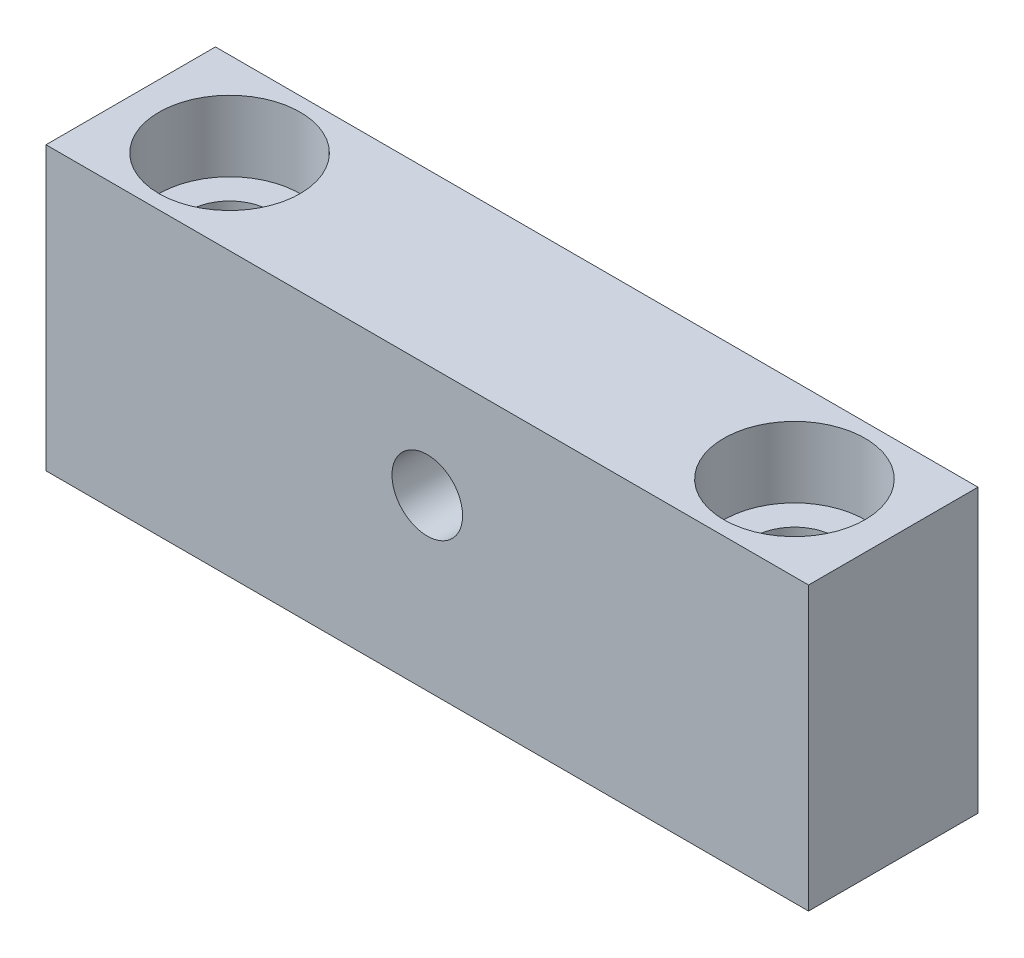
SolidWorks part; units mm, degrees
material "S45C表面镀硬铬"
ref_plane "前基準面" through (0, 0, 0) normal (0, 0, 1) x (1, 0, 0)
ref_plane "上基準面" through (0, 0, 0) normal (0, 1, 0) x (1, 0, 0)
ref_plane "右基準面" through (0, 0, 0) normal (1, 0, 0) x (0, 0, -1)
sketch "草图1" plane through (0, 0, 0) normal (0, 0, 1) x (1, 0, 0)
  line L1 (0, 0) -> (54, 0)
  line L2 (0, 0) -> (0, 20)
  line L3 (0, 20) -> (54, 20)
  line L4 (54, 0) -> (54, 20)
  dimension "D1" = 54
  dimension "D2" = 20
extrude "凸台-拉伸1" add sketch "草图1" along normal blind 12
hole_wizard "M6 螺纹孔1" positions "草图4" profile "草图5" tap size "M6" standard "ISO" end condition through all
sketch "草图4" plane through (0, 0, 12) normal (0, 0, 1) x (1, 0, 0)
  line L1 (27, 20) -> (27, 0) construction
  line L2 (54, 20) -> (0, 20) construction
  line L3 (0, 0) -> (54, 0) construction
  point P0 (27, 12)
  dimension "D1" = 12
sketch "草图5" plane through (27, 12, 12) normal (1, 0, 0) x (0, -1, 0)
  line L0 (0, 0) -> (0, 12)
  line L1 (0, 12) -> (2.5, 12)
  line L2 (2.5, 12) -> (2.5, 0)
  line L5 (2.5, 0) -> (0, 0)
  line L11 (0, -6.35) -> (0, 107.95) construction
  dimension "通孔螺纹孔钻头直径" = 5
  dimension "通孔螺纹孔钻头深度" = 12
cosmetic thread "孔螺蚊线1" parameters "D2"=6
hole_wizard "M5 六角凹头螺钉的柱形沉头孔1" positions "草图7" profile "草图6" counterbore size "M5" standard "ISO" end condition through all
sketch "草图7" plane through (0, 20, 0) normal (0, 1, 0) x (-1, 0, 0)
  line L0 (-54, 6) -> (0, 6) construction
  line L1 (-54, 12) -> (-54, 0) construction
  line L2 (0, 12) -> (0, 0) construction
  line L3 (-27, 0) -> (-27, 12) construction
  line L4 (-54, 0) -> (0, 0) construction
  line L5 (-54, 12) -> (0, 12) construction
  point P0 (-47, 6)
  point P1 (-7, 6)
  dimension "D1" = 40
sketch "草图6" plane through (47, 20, 6) normal (1, 0, 0) x (0, 0, 1)
  line L0 (0, 0) -> (0, 20)
  line L1 (0, 20) -> (2.9, 20)
  line L3 (2.9, 20) -> (2.9, 5)
  line L4 (2.9, 5) -> (5, 5)
  line L5 (5, 5) -> (5, 0)
  line L7 (5, 0) -> (0, 0)
  line L11 (0, -6.35) -> (0, 107.95) construction
  dimension "通孔孔直径" = 5.8
  dimension "通孔孔深度" = 20
  dimension "柱形沉头孔直径" = 10
  dimension "柱形沉头孔深度" = 5
